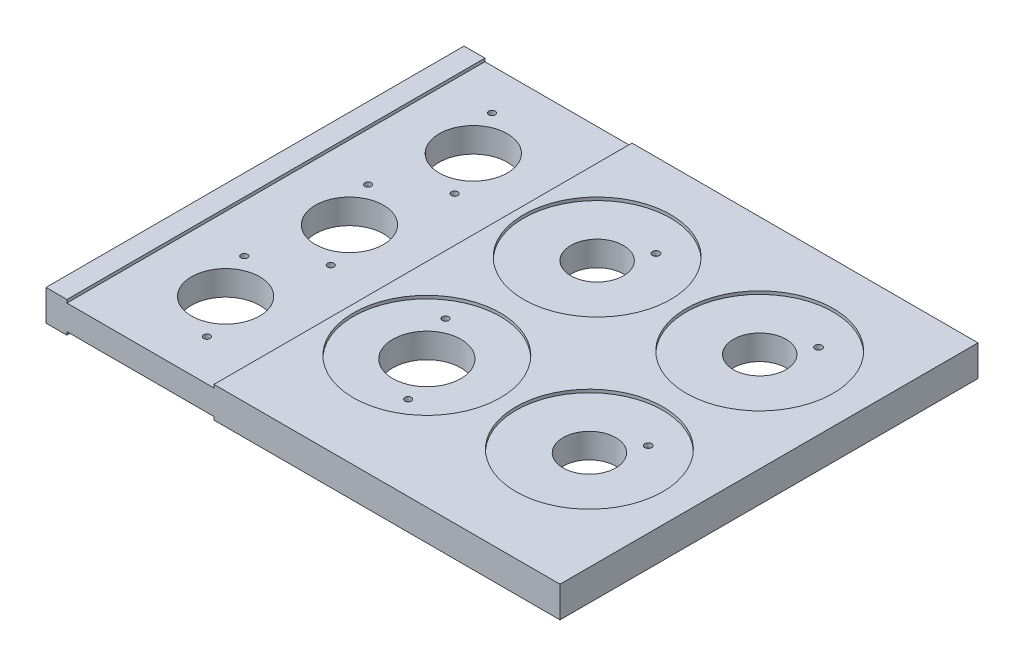
SolidWorks part; units mm, degrees
ref_plane "前视基准面" through (0, 0, 0) normal (0, 0, 1) x (1, 0, 0)
ref_plane "上视基准面" through (0, 0, 0) normal (0, 1, 0) x (1, 0, 0)
ref_plane "右视基准面" through (0, 0, 0) normal (1, 0, 0) x (0, 0, -1)
sketch "草图1" plane through (0, 0, 0) normal (0, 1, 0) x (1, 0, 0)
  line L1 (166, -135) -> (-166, -135)
  line L2 (166, -135) -> (166, 135)
  line L3 (166, 135) -> (-166, 135)
  line L4 (-166, -135) -> (-166, 135)
  line L5 (166, -135) -> (-166, 135) construction
  line L6 (166, 135) -> (-166, -135) construction
  point P0 (0, 0)
  dimension "D1" = 332
  dimension "D2" = 270
extrude "凸台-拉伸1" add sketch "草图1" along normal blind 20
sketch "草图2" plane through (0, 20, 0) normal (0, 1, 0) x (1, 0, 0)
  line L1 (-152.5, 143.9647) -> (-57.5, 143.9647)
  line L2 (-152.5, 143.9647) -> (-152.5, -145.7665)
  line L3 (-152.5, -145.7665) -> (-57.5, -145.7665)
  line L4 (-57.5, 143.9647) -> (-57.5, -145.7665)
  line L5 (166, -135) -> (166, 135) construction
  dimension "D1" = 318.5
  dimension "D2" = 95
  dimension "D3" = 289.7312
extrude "切除-拉伸1" cut sketch "草图2" against normal blind 2
sketch "草图3" plane through (0, 0, 0) normal (0, -1, 0) x (1, 0, 0)
  line L0 (-152.5, -143.9647) -> (-57.5, -143.9647) construction
  line L1 (-57.5, -143.9647) -> (-57.5, 145.7665) construction
  line L2 (-152.5, -143.9647) -> (-152.5, 145.7665) construction
  line L3 (-152.5, 145.7665) -> (-57.5, 145.7665) construction
  line L4 (-152.5, -143.9647) -> (-57.5, -143.9647)
  line L5 (-57.5, -143.9647) -> (-57.5, 145.7665)
  line L6 (-152.5, -143.9647) -> (-152.5, 145.7665)
  line L7 (-152.5, 145.7665) -> (-57.5, 145.7665)
extrude "切除-拉伸2" cut sketch "草图3" against normal blind 2
sketch "草图4" plane through (0, 20, 0) normal (0, 1, 0) x (1, 0, 0)
  line L0 (-105, 135) -> (-105, -135) construction
  line L1 (-57.5, 135) -> (-152.5, 135) construction
  line L2 (-152.5, -135) -> (-57.5, -135) construction
  line L3 (-152.5, 135) -> (-166, 135) construction
  line L4 (166, -135) -> (166, 135) construction
  line L5 (166, 135) -> (-57.5, 135) construction
  circle A0 centre (-5, 60) radius 17
  circle A1 centre (-5, -50) radius 22
  circle A2 centre (100, -50) radius 17
  circle A3 centre (100, 60) radius 17
  circle A4 centre (-105, 80) radius 22
  circle A5 centre (-105, 0) radius 22
  circle A6 centre (-105, -80) radius 22
  point P20 (0, 0)
  point P21 (0, 0)
  point P22 (0, 0)
  point P23 (0, 0)
  point P30 (0, 0)
  point P31 (0, 0)
  point P32 (0, 0)
  point P33 (0, 0)
  dimension "D1" = 34
  dimension "D2" = 44
  dimension "D3" = 55
  dimension "D4" = 80
  dimension "D5" = 80
  dimension "D6" = 66
  dimension "D7" = 105
  dimension "D8" = 75
  dimension "D9" = 110
extrude "切除-拉伸3" cut sketch "草图4" against normal up to next
sketch "草图5" plane through (0, 20, 0) normal (0, 1, 0) x (1, 0, 0)
  circle A0 centre (-5, 60) radius 47.5
  circle A1 centre (100, 60) radius 47.5
  circle A2 centre (100, -50) radius 47.5
  circle A3 centre (-5, -50) radius 47.5
  dimension "D1" = 95
extrude "切除-拉伸4" cut sketch "草图5" against normal blind 2
sketch "草图6" plane through (0, 0, 0) normal (0, -1, 0) x (1, 0, 0)
  circle A0 centre (-5, -60) radius 47.5 construction
  circle A1 centre (100, -60) radius 47.5 construction
  circle A2 centre (100, 50) radius 47.5 construction
  circle A3 centre (-5, 50) radius 47.5 construction
  circle A4 centre (-5, -60) radius 47.5
  circle A5 centre (100, -60) radius 47.5
  circle A6 centre (100, 50) radius 47.5
  circle A7 centre (-5, 50) radius 47.5
extrude "切除-拉伸5" cut sketch "草图6" against normal blind 2
sketch "草图8" plane through (0, 20, 0) normal (0, 1, 0) x (1, 0, 0)
  line L0 (-5, -50) -> (47.4346, -50) construction
  line L1 (-105, -80) -> (-68.1949, -80) construction
  line L2 (-105, 0) -> (-64.8311, 0) construction
  line L3 (-105, 80) -> (-64.8311, 80) construction
  line L4 (-5, -50) -> (11.5, -78.5788) construction
  line L5 (-5, -50) -> (11.5, -78.5788) construction
  line L6 (-105, -80) -> (-88.5, -108.5788) construction
  line L7 (-105, 0) -> (-88.5, -28.5788) construction
  line L8 (-105, -80) -> (-88.5, -108.5788) construction
  line L10 (-105, 80) -> (-88.5, 51.4212) construction
  circle A0 centre (-5, -50) radius 33 construction
  circle A1 centre (-105, -80) radius 33 construction
  circle A2 centre (-105, 0) radius 33 construction
  circle A3 centre (-105, 80) radius 33 construction
  circle A4 centre (11.5, -78.5788) radius 2.1
  circle A6 centre (-21.5, -21.4212) radius 2.1
  circle A9 centre (-88.5, -108.5788) radius 2.1
  circle A10 centre (-88.5, -28.5788) radius 2.1
  circle A11 centre (-88.5, 51.4212) radius 2.1
  circle A12 centre (-121.5, 108.5788) radius 2.1
  circle A13 centre (-121.5, 28.5788) radius 2.1
  circle A14 centre (-121.5, -51.4212) radius 2.1
  point P31 (0, 0)
  point P33 (-105, 80)
  point P36 (-105, 0)
  dimension "D1" = 66
  dimension "D2" = 4.2
  dimension "D3" = 60
  dimension "D5" = 60
  dimension "D6" = 60
  dimension "D7" = 60
  dimension "D4" = 2
  dimension "D8" = 2
  dimension "D9" = 2
  dimension "D10" = 2
extrude "切除-拉伸6" cut sketch "草图8" against normal blind 12
sketch "草图9" plane through (0, 20, 0) normal (0, 1, 0) x (1, 0, 0)
  line L0 (-5, 60) -> (-5, 116.9375) construction
  line L1 (-5, 60) -> (47.5678, 60) construction
  line L2 (100, 60) -> (143.0638, 60) construction
  line L3 (100, 60) -> (100, 112.9735) construction
  line L4 (100, -50) -> (100, -9.5496) construction
  line L5 (100, -50) -> (134.7755, -50) construction
  circle A0 centre (10, 83) radius 2.25
  circle A1 centre (115, 83) radius 2.25
  circle A2 centre (115, -27) radius 2.25
  point P18 (-5, 88.4688)
  dimension "D7" = 4.5
  dimension "D1" = 15
  dimension "D2" = 23
  dimension "D3" = 15
  dimension "D4" = 23
  dimension "D5" = 23
  dimension "D6" = 15
extrude "切除-拉伸7" cut sketch "草图9" against normal blind 5
